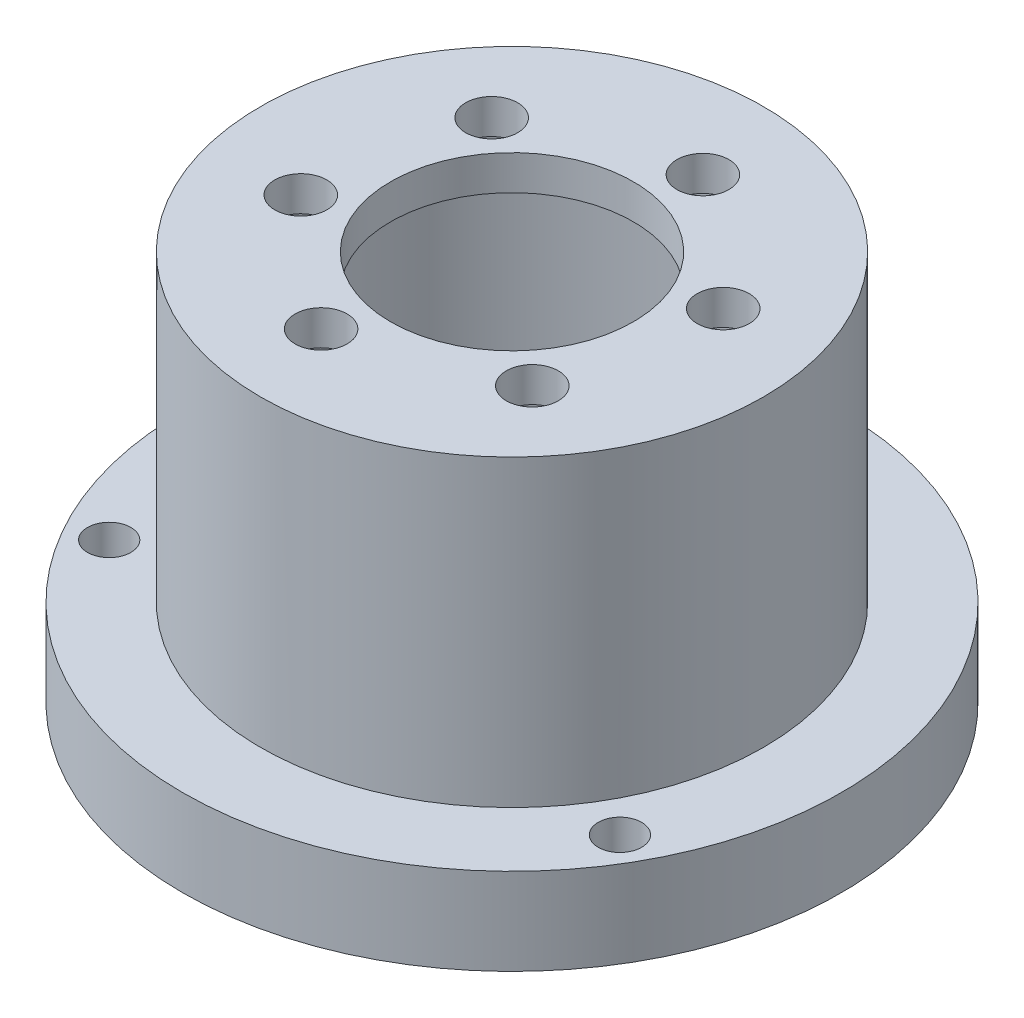
SolidWorks part; units mm, degrees
material "6061 合金"
ref_plane "前视基准面" through (0, 0, 0) normal (0, 0, 1) x (1, 0, 0)
ref_plane "上视基准面" through (0, 0, 0) normal (0, 1, 0) x (1, 0, 0)
ref_plane "右视基准面" through (0, 0, 0) normal (1, 0, 0) x (0, 0, -1)
other "Configuration Table"
sketch "草图1" plane through (0, 0, 0) normal (0, 1, 0) x (1, 0, 0)
  circle A0 centre (0, 0) radius 17 construction
  circle A1 centre (0, 0) radius 13
  circle A2 centre (0, 0) radius 19
  circle A3 centre (0, 17) radius 1.25
  circle A4 centre (14.7224, -8.5) radius 1.25
  circle A5 centre (-14.7224, -8.5) radius 1.25
  point P14 (0, 0)
  dimension "D1" = 34
  dimension "D2" = 26
  dimension "D3" = 38
  dimension "D4" = 2.5
  dimension "D5" = 3
extrude "凸台-拉伸1" add sketch "草图1" along normal blind 5
sketch "草图2" plane through (0, 5, 0) normal (0, 1, 0) x (1, 0, 0)
  circle A0 centre (0, 0) radius 13 construction
  circle A1 centre (0, 0) radius 13
extrude "拉伸-薄壁1" add sketch "草图2" along normal blind 15.5 thin
sketch "草图3" plane through (0, 20.5, 0) normal (0, 1, 0) x (1, 0, 0)
  line L0 (0, 9.5) -> (0, 0) construction
  line L1 (0, 0) -> (1.6497, 9.3557) construction
  circle A0 centre (0, 0) radius 14.5 construction
  circle A1 centre (0, 0) radius 14.5
  circle A2 centre (0, 0) radius 13 construction
  circle A3 centre (0, 0) radius 13
  circle A4 centre (0, 0) radius 9.5 construction
  circle A5 centre (1.6497, 9.3557) radius 1.5
  circle A6 centre (8.9271, 3.2492) radius 1.5
  circle A7 centre (7.2774, -6.1065) radius 1.5
  circle A8 centre (-1.6497, -9.3557) radius 1.5
  circle A9 centre (-8.9271, -3.2492) radius 1.5
  circle A10 centre (-7.2774, 6.1065) radius 1.5
  circle A11 centre (0, 0) radius 7
  point P21 (0, 0)
  circle M9 centre (0, 0) radius 14.5
  circle M10 centre (0, 0) radius 13
  dimension "D1" = 19
  dimension "D2" = 3
  dimension "D4" = 14
  dimension "D5" = 10
  dimension "D3" = 6
extrude "凸台-拉伸2" add sketch "草图3" along normal blind 2 contours A11 A10 A9 A8 A7 A6 A5 M10 | M9 M10
